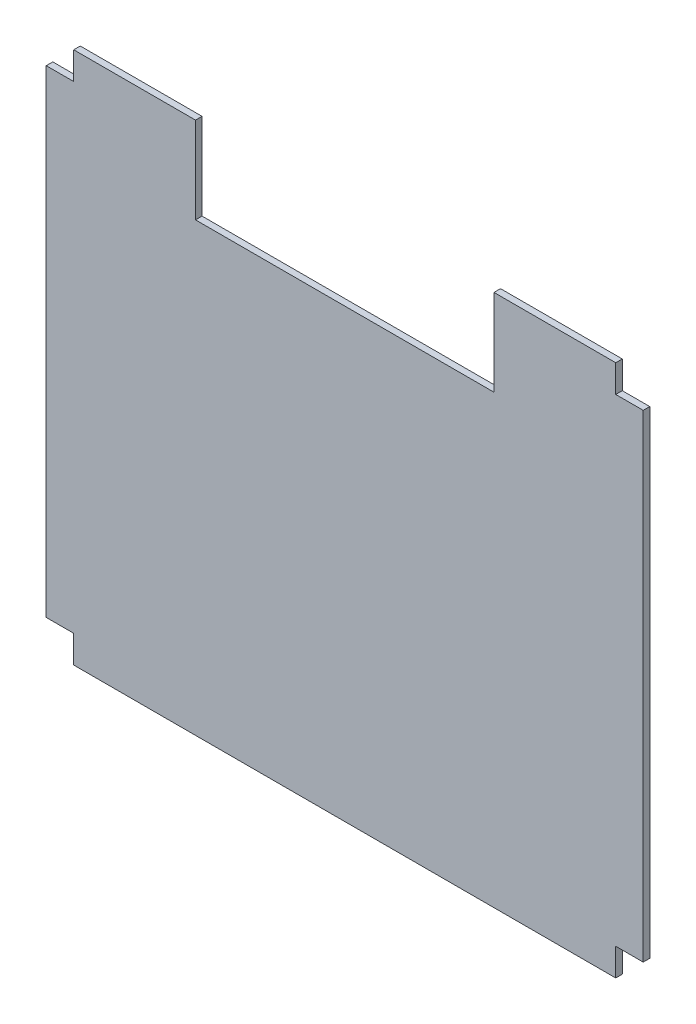
SolidWorks part; units mm, degrees
ref_plane "Front Plane" through (0, 0, 0) normal (0, 0, 1) x (1, 0, 0)
ref_plane "Top Plane" through (0, 0, 0) normal (0, 1, 0) x (1, 0, 0)
ref_plane "Right Plane" through (0, 0, 0) normal (1, 0, 0) x (0, 0, -1)
sketch "Sketch1" plane through (0, 0, 0) normal (0, 0, 1) x (1, 0, 0)
  line L0 (-114, 137.5) -> (-114, 203.5)
  line L1 (-228, -203.5) -> (228, -203.5)
  line L2 (-228, -203.5) -> (-228, 203.5)
  line L3 (-228, 203.5) -> (228, 203.5)
  line L4 (228, -203.5) -> (228, 203.5)
  line L5 (-228, -203.5) -> (0, 0) construction
  line L6 (-228, 203.5) -> (-207, 184.7566) construction
  line L7 (-207, 203.5) -> (-114, 203.5)
  line L8 (-207, 203.5) -> (-207, 182.5)
  line L11 (114, 203.5) -> (207, 203.5)
  line L14 (207, 203.5) -> (207, 182.5)
  line L15 (-207, 182.5) -> (-228, 182.5)
  line L17 (-207, -182.5) -> (-228, -182.5)
  line L18 (-228, 182.5) -> (-228, -182.5)
  line L19 (207, 182.5) -> (228, 182.5)
  line L20 (207, 182.5) -> (207, 142.5)
  line L21 (207, -182.5) -> (228, -182.5)
  line L22 (228, 182.5) -> (228, -182.5)
  line L27 (114, 137.5) -> (114, 203.5)
  line L31 (207, 182.5) -> (207, 142.5)
  line L32 (0, 0) -> (228, -203.5) construction
  line L33 (-207, -182.5) -> (-204.4717, -182.5)
  line L34 (-207, -182.5) -> (-207, -203.5)
  line L35 (-207, -203.5) -> (207, -203.5)
  line L36 (207, -182.5) -> (207, -203.5)
  line L37 (-114, 137.5) -> (114, 137.5)
  line L38 (207, 184.7566) -> (228, 203.5) construction
  line L39 (204.4717, -182.5) -> (207, -182.5)
  line L40 (0, 203.5) -> (0, -203.5) construction
  point P0 (0, 0)
  dimension "D1" = 456
  dimension "D2" = 407
  dimension "D3" = 21
  dimension "D4" = 66
  dimension "D5" = 21
  dimension "D6" = 93
  dimension "D7" = 21
  dimension "D8" = 21
  dimension "D9" = 21
  dimension "D10" = 21
  dimension "D11" = 21
extrude "Boss-Extrude1" add sketch "Sketch1" along normal blind 5
